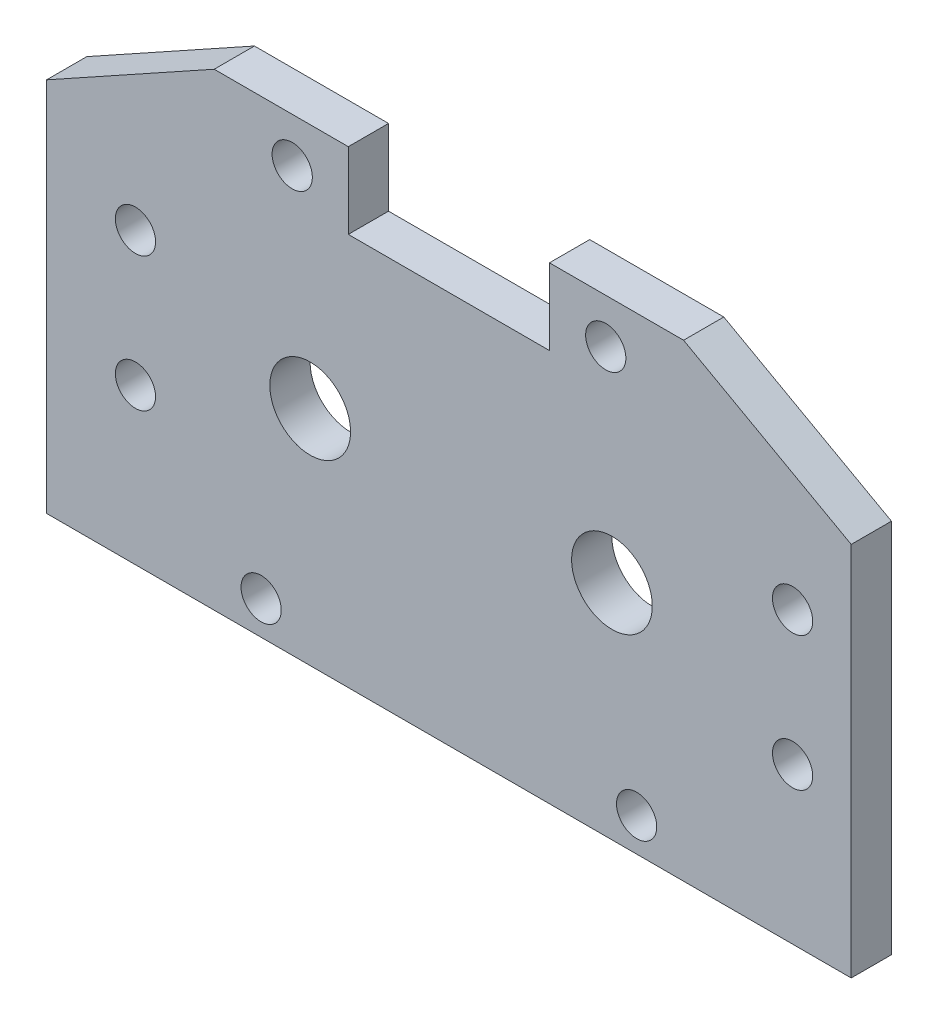
SolidWorks part; units mm, degrees
ref_plane "前视基准面" through (0, 0, 0) normal (0, 0, 1) x (1, 0, 0)
ref_plane "上视基准面" through (0, 0, 0) normal (0, 1, 0) x (1, 0, 0)
ref_plane "右视基准面" through (0, 0, 0) normal (1, 0, 0) x (0, 0, -1)
sketch "草图1" plane through (0, 0, 0) normal (0, 0, 1) x (1, 0, 0)
  line L0 (-7.5, 0) -> (7.5, 0)
  line L1 (7.5, 0) -> (7.5, 5.6658)
  line L2 (7.5, 5.6658) -> (17.5, 5.6658)
  line L3 (17.5, 5.6658) -> (30, -1.2693)
  line L4 (30, -1.2693) -> (30, -29.2693)
  line L5 (30, -29.2693) -> (-30, -29.2693)
  line L6 (0, 0) -> (0, -29.2693) construction
  line L7 (-30, -1.2693) -> (-30, -29.2693)
  line L8 (-7.5, 0) -> (-7.5, 5.6658)
  line L9 (-7.5, 5.6658) -> (-17.5, 5.6658)
  line L10 (-17.5, 5.6658) -> (-30, -1.2693)
  dimension "D1" = 30
  dimension "D2" = 7.5
  dimension "D3" = 10
  dimension "D4" = 28
extrude "凸台-拉伸1" add sketch "草图1" along normal blind 3
sketch "草图2" plane through (0, 0, 0) normal (0, 0, -1) x (-1, 0, 0)
  circle A0 centre (-25.6284, -17.6694) radius 1.5
  circle A1 centre (-25.6284, -7.6694) radius 1.5
  circle A2 centre (23.3716, -17.6694) radius 1.5
  circle A3 centre (23.3716, -7.6694) radius 1.5
  dimension "D1" = 3
  dimension "D2" = 3
  dimension "D3" = 3
  dimension "D4" = 3
extrude "切除-拉伸7" cut sketch "草图2" against normal through all
sketch "草图4" plane through (0, 0, 0) normal (0, 0, -1) x (-1, 0, 0)
  circle A0 centre (-11.6968, 2.3503) radius 1.5
  circle A1 centre (11.6822, 2.3503) radius 1.5
  dimension "D1" = 3
  dimension "D2" = 3
extrude "切除-拉伸8" cut sketch "草图4" against normal through all
sketch "草图5" plane through (0, 0, 0) normal (0, 0, -1) x (-1, 0, 0)
  circle A0 centre (10.3416, -12.6693) radius 3.01
  circle A1 centre (-12.1584, -12.6694) radius 3.01
extrude "切除-拉伸9" cut sketch "草图5" against normal through all
sketch "草图6" plane through (0, 0, 0) normal (0, 0, -1) x (-1, 0, 0)
  line L0 (30, -1.2693) -> (30, -29.2693) construction
  line L1 (-30, -29.2693) -> (-30, -1.2693) construction
  line L2 (30, -29.2693) -> (-30, -29.2693) construction
  circle A0 centre (14, -26.7693) radius 1.5
  circle A1 centre (-14, -26.7693) radius 1.5
  dimension "D1" = 16
  dimension "D2" = 16
  dimension "D3" = 2.5
  dimension "D4" = 2.5
  dimension "D5" = 3
  dimension "D6" = 3
extrude "切除-拉伸10" cut sketch "草图6" against normal through all
